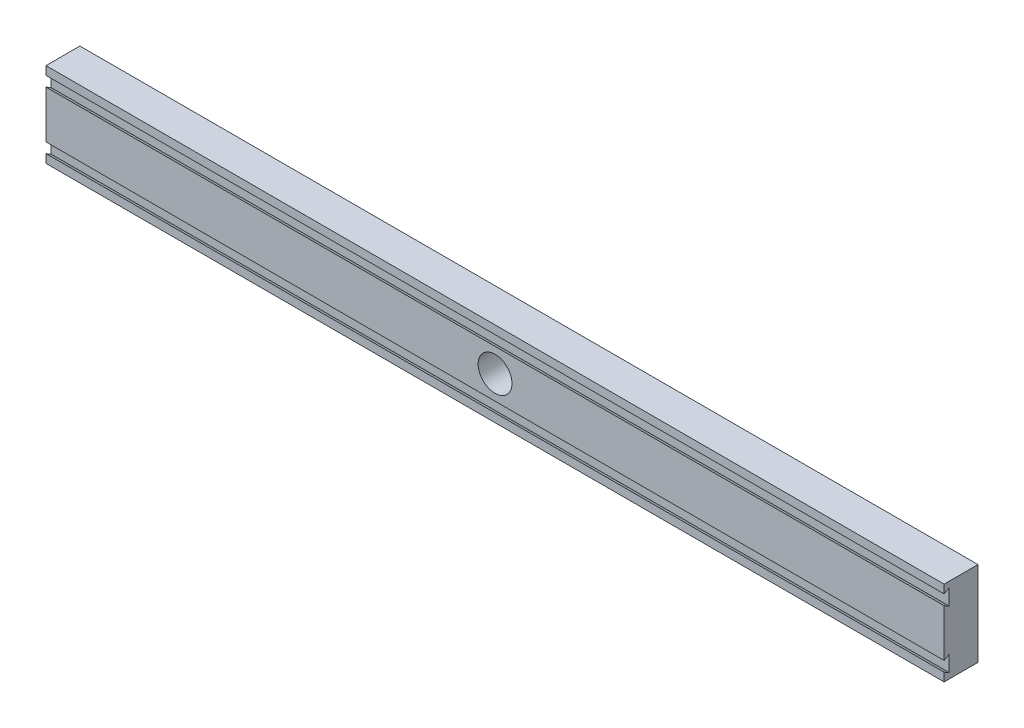
SolidWorks part; units mm, degrees
ref_plane "Front Plane" through (0, 0, 0) normal (0, 0, 1) x (1, 0, 0)
ref_plane "Top Plane" through (0, 0, 0) normal (0, 1, 0) x (1, 0, 0)
ref_plane "Right Plane" through (0, 0, 0) normal (1, 0, 0) x (0, 0, -1)
sketch "Sketch2" plane through (0, 0, 0) normal (1, 0, 0) x (0, 0, -1)
  line L0 (-10, 0) -> (10, 0) construction
  line L1 (-10, -25) -> (10, -25)
  line L2 (-10, -25) -> (-10, 25)
  line L3 (-10, 25) -> (10, 25)
  line L4 (10, -25) -> (10, 25)
  line L5 (-10, -25) -> (10, 25) construction
  line L6 (-10, 25) -> (10, -25) construction
  line L7 (-10, 14) -> (-10, 20)
  line L8 (-10, 20) -> (-7, 21.7321)
  line L9 (-7, 21.7321) -> (-7, 12.2679)
  line L10 (-7, 12.2679) -> (-10, 14)
  line L11 (-7, -12.2679) -> (-10, -14)
  line L12 (-7, -21.7321) -> (-7, -12.2679)
  line L13 (-10, -20) -> (-7, -21.7321)
  line L14 (-10, -20) -> (-10, -14)
  point P0 (0, 0)
  dimension "D1" = 50
  dimension "D2" = 20
  dimension "D3" = 6
  dimension "D4" = 60
  dimension "D5" = 60
  dimension "D6" = 5
  dimension "D7" = 3
extrude "Boss-Extrude1" add sketch "Sketch2" along normal mid plane 530 contours L13 L2 L1 L4 L3 L8 L9 L10 L11 L12
sketch "Sketch3" plane through (0, 0, 0) normal (0, 0, 1) x (1, 0, 0)
  circle A0 centre (0, 0) radius 10
  dimension "D1" = 20
extrude "Cut-Extrude2" cut sketch "Sketch3" against normal through all both and the other way through all
scale "Scale2" scale about centroid uniform scaling yes scale factor 0.2004
